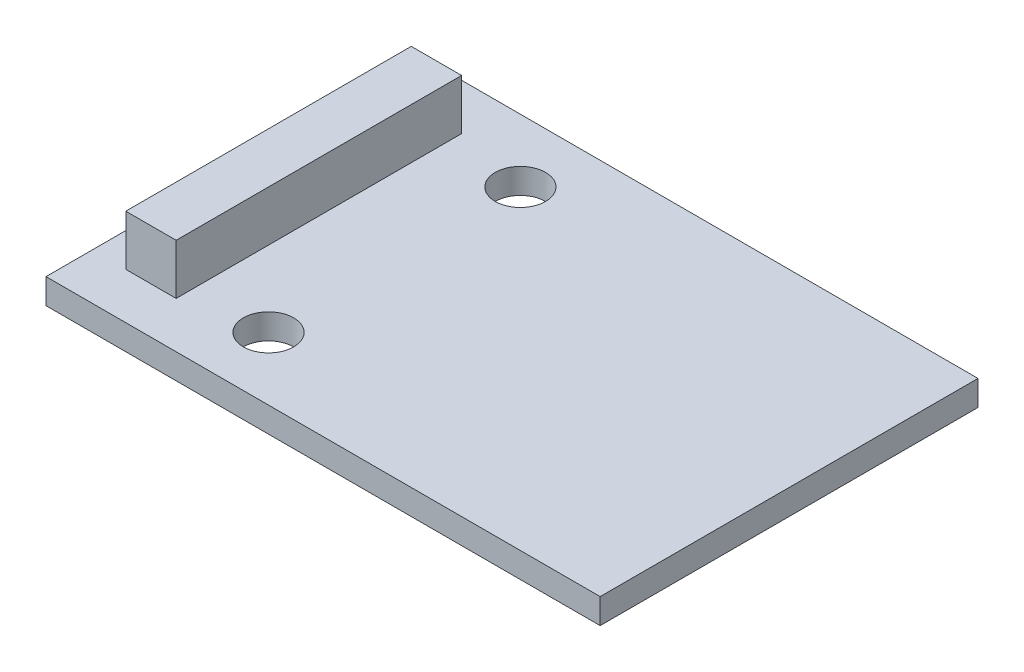
SolidWorks part; units mm, degrees
ref_plane "Front Plane" through (0, 0, 0) normal (0, 0, 1) x (1, 0, 0)
ref_plane "Top Plane" through (0, 0, 0) normal (0, 1, 0) x (1, 0, 0)
ref_plane "Right Plane" through (0, 0, 0) normal (1, 0, 0) x (0, 0, -1)
sketch "Sketch1" plane through (0, 0, 0) normal (0, 1, 0) x (1, 0, 0)
  line L0 (-51.1158, -30.8065) -> (-18.1158, -30.8065) construction
  line L1 (-51.1158, -42.0565) -> (-18.1158, -42.0565)
  line L2 (-51.1158, -42.0565) -> (-51.1158, -19.5565)
  line L3 (-51.1158, -19.5565) -> (-18.1158, -19.5565)
  line L4 (-18.1158, -42.0565) -> (-18.1158, -19.5565)
  line L5 (-41.6158, -23.3065) -> (-41.6158, -30.8065) construction
  line L6 (-41.6158, -30.8065) -> (-41.6158, -38.3065) construction
  circle A0 centre (-41.6158, -38.3065) radius 1.5
  circle A1 centre (-41.6158, -23.3065) radius 1.5
  dimension "D3" = 3
  dimension "D4" = 3
  dimension "D5" = 7.5
  dimension "D6" = 7.5
  dimension "D8" = 9.5
  dimension "D1" = 22.5
  dimension "D2" = 33
  dimension "D7" = 9.5
extrude "Boss-Extrude1" add sketch "Sketch1" along normal blind 1.5
sketch "Sketch2" plane through (0, 1.5, 0) normal (0, 1, 0) x (1, 0, 0)
  line L0 (-51.1158, -30.8065) -> (-29.483, -30.8065) construction
  line L1 (-46.1158, -39.3065) -> (-49.1158, -39.3065)
  line L2 (-46.1158, -39.3065) -> (-46.1158, -22.3065)
  line L3 (-46.1158, -22.3065) -> (-49.1158, -22.3065)
  line L4 (-49.1158, -39.3065) -> (-49.1158, -22.3065)
  line L5 (-51.1158, -19.5565) -> (-51.1158, -42.0565) construction
  line L6 (-49.1158, -30.8065) -> (-37.7404, -30.8065) construction
  dimension "D1" = 17
  dimension "D2" = 3
  dimension "D3" = 2
extrude "Boss-Extrude2" add sketch "Sketch2" along normal blind 3
